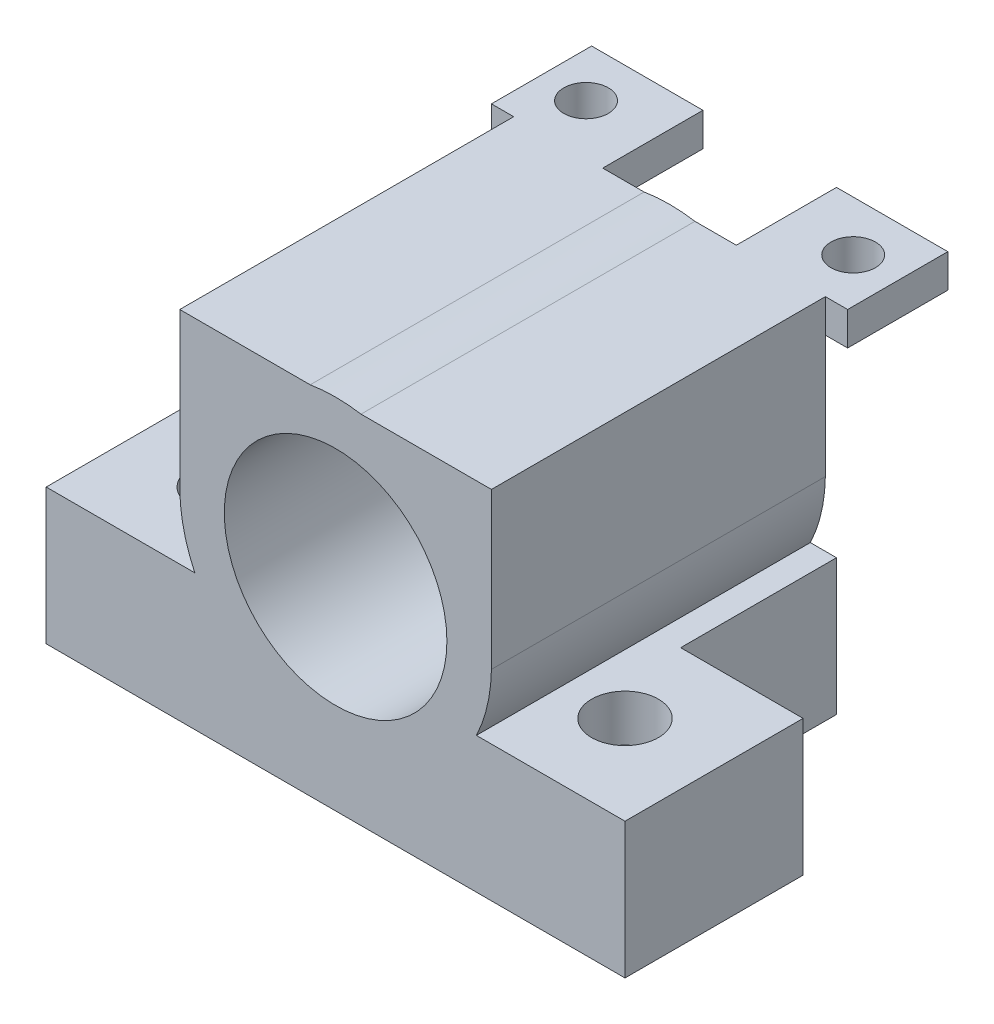
SolidWorks part; units mm, degrees
ref_plane "Plano frontal" through (0, 0, 0) normal (0, 0, 1) x (1, 0, 0)
ref_plane "Plano superior" through (0, 0, 0) normal (0, 1, 0) x (1, 0, 0)
ref_plane "Plano direito" through (0, 0, 0) normal (1, 0, 0) x (0, 0, -1)
sketch "Esboço4" plane through (0, 0, 0) normal (0, 0, 1) x (1, 0, 0)
  line L0 (0, -5) -> (13, -5)
  line L1 (0, -5) -> (-13, -5)
  line L2 (6.3246, -3) -> (13, -3)
  line L3 (-6.3246, -3) -> (-13, -3)
  line L4 (0, -3) -> (-13, -3) construction
  line L5 (0, -3) -> (13, -3) construction
  line L6 (-13, -3) -> (-13, -5)
  line L7 (13, -3) -> (13, -5)
  circle A0 centre (0, 0) radius 5
  arc A1 (6.3246, -3) -> (-6.3246, -3) centre (0, 0) ccw
  circle A2 centre (0, 0) radius 7 construction
  dimension "D1" = 10
  dimension "D2" = 13
  dimension "D3" = 13
  dimension "D4" = 2
extrude "Ressalto-extrusão4" add sketch "Esboço4" along normal blind 8 contours L2 A1 L3 L6 L1 A0 L0 L7 | A0
sketch "Esboço7" plane through (0, -5, 0) normal (0, -1, 0) x (1, 0, 0)
  line L0 (-13, 8) -> (13, 8)
  line L2 (-13, 8) -> (-13, 0)
  line L3 (-13, 0) -> (13, 0)
  line L4 (13, 0) -> (13, 8)
extrude "Ressalto-extrusão5" add sketch "Esboço7" along normal blind 0.1
sketch "Esboço8" plane through (0, 0, 8) normal (0, 0, 1) x (1, 0, 0)
  circle A0 centre (0, 0) radius 5
  dimension "D1" = 10
extrude "Corte-extrusão7" cut sketch "Esboço8" against normal through all
sketch "Esboço9" plane through (0, 0, 0) normal (0, 0, -1) x (-1, 0, 0)
  line L2 (-13, -3) -> (-13, -5.1)
  line L3 (13, -3) -> (13, -5.1)
  line L5 (0, -5.1) -> (7.5, -5.1)
  line L6 (13, -5.1) -> (-13, -5.1) construction
  line L7 (0, -5.1) -> (-7.5, -5.1)
  line L8 (0, -3) -> (4, -3)
  line L9 (6.3246, -3) -> (7.5, -3)
  line L10 (-7.5, -3) -> (-7.5, -5.1)
  line L11 (7.5, -3) -> (7.5, -5.1)
  line L12 (-6.3246, -3) -> (-7.5, -3)
  line L13 (0, -3) -> (-7.5, -3) construction
  line L14 (0, -3) -> (7.5, -3) construction
  line L15 (-7.5, -5.1) -> (7.5, -5.1)
  arc A0 (4, -3) -> (-4, -3) centre (0, 0) ccw
  arc A5 (6.3246, -3) -> (-6.3246, -3) centre (0, 0) ccw
  circle M2 centre (0, 0) radius 5
  line M3 (-6.3246, -3) -> (-13, -3)
  line M5 (-13, -5.1) -> (13, -5.1)
  line M7 (13, -3) -> (6.3246, -3)
  arc M8 (6.3246, -3) -> (-6.3246, -3) centre (0, 0) ccw
  dimension "D1" = 7.5
  dimension "D2" = 7.5
  dimension "D3" = 2.1
extrude "Ressalto-extrusão6" add sketch "Esboço9" along normal blind 7 contours L11 L10 M7 M8 M3 M5 M2
sketch "Esboço10" plane through (0, -3, 0) normal (0, 1, 0) x (1, 0, 0)
  line L0 (-6.3246, -8) -> (-13, -8) construction
  line L1 (-13, -8) -> (-13, 0) construction
  line L2 (6.3246, -8) -> (13, -8) construction
  line L3 (13, -8) -> (13, 0) construction
  circle A0 centre (-9, -4) radius 1.5
  circle A1 centre (9, -4) radius 1.5
  dimension "D3" = 3
  dimension "D6" = 3
  dimension "D1" = 4
  dimension "D2" = 4
  dimension "D4" = 4
  dimension "D5" = 4
extrude "Corte-extrusão8" cut sketch "Esboço10" against normal through all
sketch3d "3DSketch1"
  point P0 (1.1412, 6.9063, 1.5699)
ref_plane "Plano1" through (0, 6.9063, 0) normal (0, 1, 0) x (0, 0, -1)
sketch "Esboço11" plane through (0, 6.9063, 0) normal (0, 1, 0) x (0, 0, -1)
  line L0 (7, 7) -> (-8, 7)
  line L1 (-8, 7) -> (-8, -7)
  line L2 (-8, -7) -> (7, -7)
  line L3 (-8, -7) -> (7, -7) construction
  line L4 (7, -7) -> (7, 7) construction
  line L5 (7, -7) -> (7, 7)
  line L8 (7, 7) -> (7, 3)
  line L17 (7, -7) -> (7, -3)
  line L18 (11.5, -7) -> (11.5, -8)
  line L20 (7, 7) -> (7, 3)
  line L21 (7, 3) -> (11.5, 3)
  line L22 (11.5, 7) -> (11.5, 3)
  line L23 (7, -3) -> (11.5, -3)
  line L24 (7, -3) -> (7, -7)
  line L26 (11.5, -3) -> (11.5, -7)
  line L27 (7, -7) -> (7, -8)
  line L28 (11.5, -8) -> (7, -8)
  line L29 (11.5, 7) -> (11.5, 8)
  line L30 (7, 7) -> (7, 8)
  line L31 (11.5, 8) -> (7, 8)
  line L32 (9.25, 8) -> (9.25, 6)
  line L33 (9.25, -8) -> (9.25, -6)
  circle A0 centre (9.25, 6) radius 1
  circle A1 centre (9.25, -6) radius 1
  dimension "D8" = 2
  dimension "D10" = 2
  dimension "D1" = 4
  dimension "D2" = 4
  dimension "D3" = 4.5
  dimension "D4" = 4.5
  dimension "D5" = 1
  dimension "D6" = 1
  dimension "D7" = 2
  dimension "D9" = 2
extrude "Ressalto-extrusão7" add sketch "Esboço11" against normal blind 1.5
sketch "Esboço12" plane through (0, 5.4063, 0) normal (0, -1, 0) x (1, 0, 0)
  line L0 (-7, -7) -> (8, -7)
  line L1 (-7, 8) -> (7, 8)
  line L2 (7, 8) -> (7, -7)
  line L3 (-7, 8) -> (-7, -7)
  line L4 (-4.4465, -7) -> (-4.4465, 8)
  line L5 (4.4465, -7) -> (4.4465, 8)
  line L6 (4.4465, 8) -> (4.4465, -7) construction
  line M7 (-4.4465, -7) -> (-4.4465, 8)
  line M8 (-4.4465, 8) -> (-7, 8)
  line M9 (-7, 8) -> (-7, -7)
extrude "Ressalto-extrusão9" add sketch "Esboço12" along normal blind 5.5 contours L0 M9 M7 M8 | L5 L0 L2 L1
sketch "Esboço13" plane through (0, 0, -7) normal (0, 0, -1) x (-1, 0, 0)
  circle A0 centre (0, 0) radius 5
extrude "Corte-extrusão9" cut sketch "Esboço13" against normal through all
sketch "Esboço14" plane through (0, -5.1, 0) normal (0, -1, 0) x (1, 0, 0)
  line L0 (-13, 8) -> (-13, 0)
  line L1 (-13, 0) -> (-7.5, 0)
  line L2 (-7.5, 0) -> (-7.5, -7)
  line L3 (-7, -7) -> (-8, -7) construction
  line L4 (-7.5, -7) -> (7.5, -7)
  line L5 (8, -7) -> (7, -7) construction
  line L6 (7.5, -7) -> (7.5, 0)
  line L7 (7.5, 0) -> (13, 0)
  line L8 (13, 0) -> (13, 8)
  line L9 (13, 8) -> (-13, 8)
  circle A0 centre (-9, 4) radius 1.4682
  circle A1 centre (9, 4) radius 1.4846
extrude "Ressalto-extrusão10" add sketch "Esboço14" along normal blind 4
